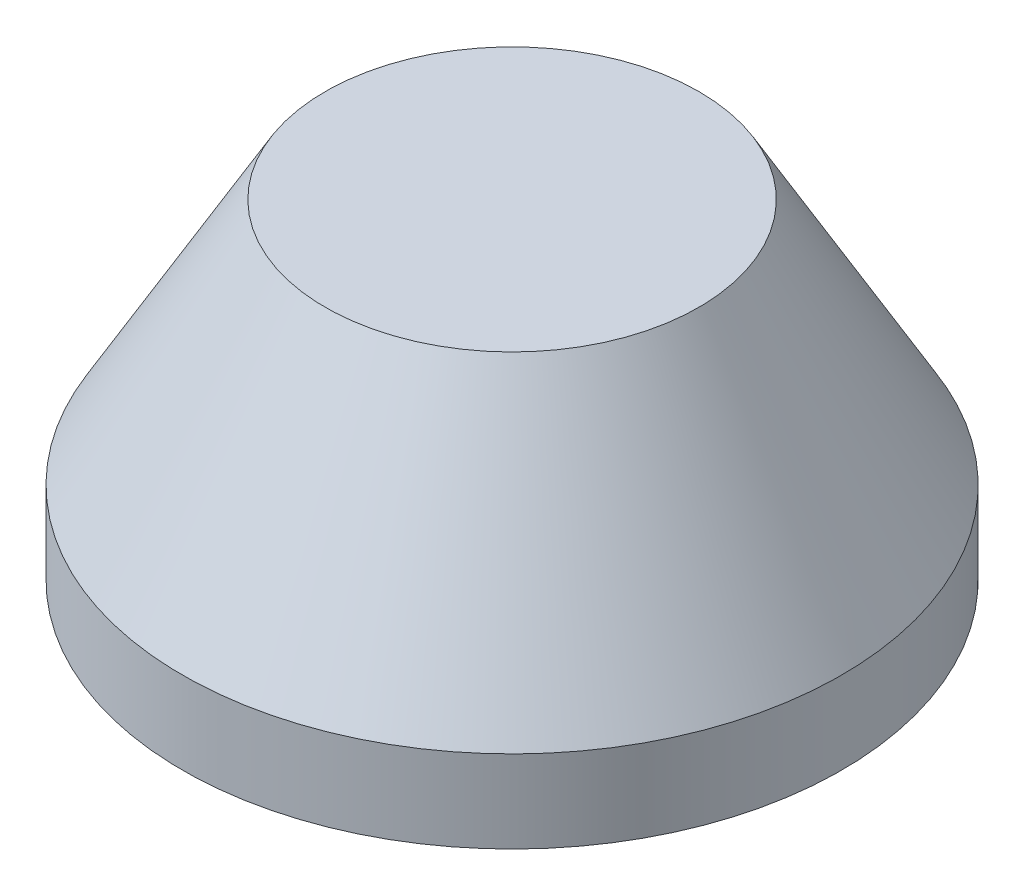
SolidWorks part; units mm, degrees
material "Custom Plastic"
ref_plane "Front Plane" through (0, 0, 0) normal (0, 0, 1) x (1, 0, 0)
ref_plane "Top Plane" through (0, 0, 0) normal (0, 1, 0) x (1, 0, 0)
ref_plane "Right Plane" through (0, 0, 0) normal (1, 0, 0) x (0, 0, -1)
other "Configuration Table"
sketch "Sketch1" plane through (0, 0, 0) normal (0, 0, 1) x (1, 0, 0)
  line L0 (0, 33.8302) -> (0, -36.8957) construction
  line L1 (0, 0) -> (-25.4, 0)
  line L2 (-25.4, 0) -> (-25.4, 6.35)
  line L3 (-25.4, 19.05) -> (-19.05, 25.4)
  line L4 (-19.05, 25.4) -> (0, 25.4)
  line L5 (0, 25.4) -> (0, 0)
  line L6 (-25.4, 12.7) -> (-25.4, 19.05)
  line L7 (-25.4, 12.7) -> (-19.05, 12.7)
  line L9 (-25.4, 6.35) -> (-19.05, 6.35)
  line L10 (-19.05, 12.7) -> (-19.05, 6.35)
  point P12 (-22.225, 6.35)
  dimension "D1" = 6.35
  dimension "D2" = 19.05
  dimension "D3" = 50.8
  dimension "D4" = 45
  dimension "D5" = 6.35
  dimension "D6" = 6.35
  dimension "D7" = 6.35
revolve "Revolve1" [suppressed] add sketch "Sketch1" angle 360 about L0
sketch "Sketch2" plane through (0, 0, 0) normal (0, 0, 1) x (1, 0, 0)
  line L0 (0, 0) -> (0, -8.9693) construction
  line L1 (0, 0) -> (-9.525, 0)
  line L2 (0, 0) -> (0, 12.7)
  line L3 (0, 12.7) -> (-9.525, 12.7)
  line L4 (-9.525, 0) -> (-9.525, 12.7)
  dimension "D1" = 19.05
  dimension "D2" = 12.7
revolve "Cut-Revolve1" [suppressed] cut sketch "Sketch2" angle 360 about L0
hole_wizard "5/8-11 Tapped Hole1" [suppressed] positions "Sketch3" profile "Sketch4" tap size "5/8-11" standard "ANSI Inch"
sketch "Sketch3" [suppressed] plane through (0, 0, 0) normal (0, -1, 0) x (-1, 0, 0)
  point P0 (0, 0)
sketch "Sketch4" plane through (0, 0, 0) normal (1, 0, 0) x (0, 0, -1)
  line L0 (0, 0) -> (0, 12.7)
  line L1 (0, 12.7) -> (6.7462, 8.6465)
  line L2 (6.7462, 8.6465) -> (6.7462, 0)
  line L5 (6.7462, 0) -> (0, 0)
  line L10 (0, 12.7) -> (-6.7462, 8.6465) construction
  line L11 (0, -6.35) -> (0, 107.95) construction
  dimension "Tap Drill Dia." = 13.4925
  dimension "Tap Drill Depth" = 12.7
  dimension "Drill Angle" = 118
cosmetic thread "Hole Thread1" [suppressed] parameters "D1"=10.3886, "D2"=15.875
sketch "Sketch5" plane through (0, 0, 0) normal (0, 0, 1) x (1, 0, 0)
  line L0 (0, 0) -> (0, 59.7933) construction
  line L1 (0, 0) -> (-25.4, 0)
  line L2 (-25.4, 0) -> (-25.4, 6.35)
  line L3 (-25.4, 6.35) -> (-14.4015, 25.4)
  line L4 (-14.4015, 25.4) -> (0, 25.4)
  line L5 (0, 0) -> (0, 25.4)
  dimension "D1" = 50.8
  dimension "D2" = 6.35
  dimension "D3" = 19.05
  dimension "D4" = 30
revolve "Revolve2" add sketch "Sketch5" angle 360 about L0
hole_wizard "5/8 (0.75) Diameter Hole1" positions "Sketch8" profile "Sketch9" hole size "5/8" standard "ANSI Inch"
sketch "Sketch8" plane through (0, 0, 0) normal (0, -1, 0) x (-1, 0, 0)
  point P0 (0, 0)
sketch "Sketch9" plane through (0, 0, 0) normal (1, 0, 0) x (0, 0, -1)
  line L0 (0, 0) -> (0, 19.05)
  line L1 (0, 19.05) -> (9.525, 13.3268)
  line L2 (9.525, 13.3268) -> (9.525, 0)
  line L5 (9.525, 0) -> (0, 0)
  line L10 (0, 19.05) -> (-9.525, 13.3268) construction
  line L11 (0, -6.35) -> (0, 107.95) construction
  dimension "Hole Dia." = 19.05
  dimension "Hole Depth" = 19.05
  dimension "Drill Angle" = 118
